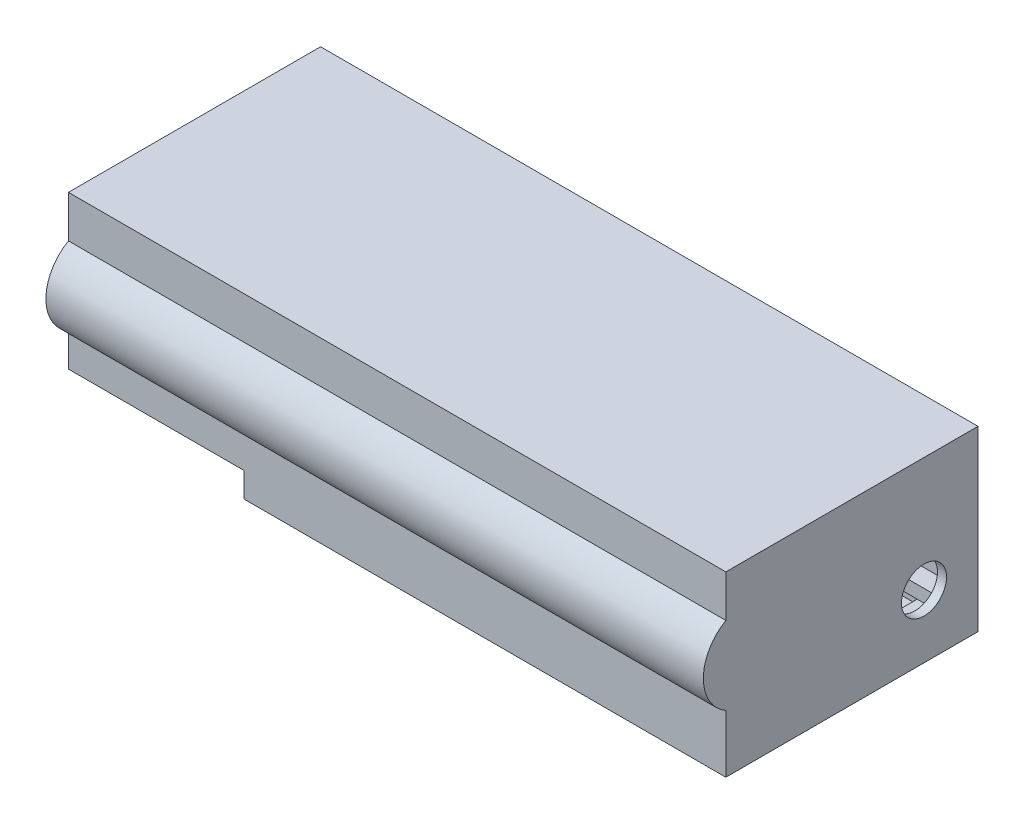
SolidWorks part; units mm, degrees
ref_plane "Front Plane" through (0, 0, 0) normal (0, 0, 1) x (1, 0, 0)
ref_plane "Top Plane" through (0, 0, 0) normal (0, 1, 0) x (1, 0, 0)
ref_plane "Right Plane" through (0, 0, 0) normal (1, 0, 0) x (0, 0, -1)
sketch "Sketch1" plane through (0, 0, 0) normal (1, 0, 0) x (0, 0, -1)
  line L0 (0, 39.5) -> (28, 39.5)
  line L1 (0, 55) -> (0, -55) construction
  line L2 (28, 39.5) -> (28, 0)
  line L3 (55, 0) -> (-55, 0) construction
  line L4 (28, 0) -> (22, 0)
  line L5 (22, 0) -> (22, 1.5)
  line L6 (22, 1.5) -> (25, 1.5)
  line L7 (25, 1.5) -> (25, 5.5)
  line L8 (25, 5.5) -> (22, 5.5)
  line L9 (22, 5.5) -> (22, 37.5)
  line L10 (22, 37.5) -> (0, 37.5)
  line L11 (0, 39.5) -> (0, 37.5)
  point P4 (0, 0)
  point P16 (0, 0)
  dimension "D1" = 2
  dimension "D2" = 6
  dimension "D3" = 3
  dimension "D4" = 22
  dimension "D5" = 4
  dimension "D6" = 1.5
  dimension "D7" = 32
extrude "Boss-Extrude1" add sketch "Sketch1" along normal blind 144
mirror "Mirror1" about plane through (0, 0, 0) normal (0, 0, 1) of "Boss-Extrude1"
sketch "Sketch2" plane through (144, 0, 0) normal (1, 0, 0) x (0, 0, -1)
  line L1 (22, 37.5) -> (26, 37.5)
  line L2 (22, 37.5) -> (22, 8.3284)
  line L3 (22, 8.3284) -> (26, 8.3284)
  line L4 (26, 37.5) -> (26, 8.3284)
  dimension "D1" = 4
  dimension "D2" = 3
extrude "Cut-Extrude1" cut sketch "Sketch2" against normal through all both and the other way through all
mirror "Mirror2" about plane through (0, 0, 0) normal (0, 0, 1) of "Cut-Extrude1"
sketch "Sketch3" plane through (144, 0, 0) normal (1, 0, 0) x (0, 0, -1)
  line L0 (-28, 0) -> (-28, 39.5) construction
  line L2 (-22, 5.5) -> (-25, 5.5) construction
  line L3 (-28, 30.1603) -> (-28, 12.8397)
  arc A0 (-28, 30.1603) -> (-28, 12.8397) centre (-23, 21.5) ccw
  point P7 (-28, 31.2777)
  dimension "D2" = 10
  dimension "D3" = 5
  dimension "D1" = 16
extrude "Boss-Extrude2" add sketch "Sketch3" against normal blind 144
sketch "Sketch4" plane through (144, 0, 0) normal (1, 0, 0) x (0, 0, -1)
  line L0 (-26, 37.5) -> (-26, 8.3284) construction
  line L1 (-26, 8.3284) -> (-22, 8.3284) construction
  line L2 (-26, 28.0366) -> (-26, 14.6202)
  arc A0 (-26, 28.0366) -> (-26, 14.6202) centre (-24, 21.3284) ccw
  dimension "D2" = 7
  dimension "D1" = 13
  dimension "D3" = 2
extrude "Cut-Extrude2" cut sketch "Sketch4" against normal through all both and the other way through all
sketch "Sketch6" plane through (0, 0, -28) normal (0, 0, -1) x (-1, 0, 0)
  line L0 (-39, 0) -> (-39, 5.5)
  line L2 (33.55, 0) -> (-33.55, 0) construction
  line L3 (-39, 5.5) -> (0, 5.5)
  line L4 (0, 21.725) -> (0, -21.725) construction
  line L5 (0, 5.5) -> (0, 0)
  line L6 (0, 0) -> (-39, 0)
  line L7 (-144, 0) -> (-144, 39.5) construction
  dimension "D1" = 105
  dimension "D2" = 5.5
extrude "Cut-Extrude3" cut sketch "Sketch6" against normal through all both and the other way through all
sketch "Sketch7" plane through (0, 0, -28) normal (0, 0, -1) x (-1, 0, 0)
  line L0 (-144, 39.5) -> (-146, 39.5)
  line L1 (-146, 39.5) -> (-146, 0)
  line L2 (33.55, 0) -> (-33.55, 0) construction
  line L3 (-146, 0) -> (-136, 0)
  line L4 (-136, 0) -> (-136, 2.9977)
  line L5 (-136, 2.9977) -> (-144, 2.9977)
  line L6 (-144, 0) -> (-144, 39.5) construction
  line L11 (-144, 2.9977) -> (-144, 39.5)
  point P3 (0, 0)
  point P13 (0, 0)
  dimension "D1" = 2.9977
  dimension "D4" = 10
  dimension "D5" = 8
extrude "Boss-Extrude3" add sketch "Sketch7" against normal up to vertex (56 mm away)
sketch "Sketch10" plane through (144, 0, 0) normal (1, 0, 0) x (0, 0, -1)
  line L0 (-28, 30.1603) -> (-28, 12.8397)
  arc A0 (-28, 30.1603) -> (-28, 12.8397) centre (-23, 21.5) ccw
  dimension "D1" = 10
extrude "Boss-Extrude5" add sketch "Sketch10" along normal blind 3
sketch "Sketch15" plane through (147, 0, 0) normal (1, 0, 0) x (0, 0, -1)
  line L0 (-28, 12.8397) -> (-28, 30.1603)
  arc A0 (-28, 12.8397) -> (-28, 30.1603) centre (-23, 21.5) cw
  dimension "D1" = 10
extrude "Cut-Extrude5" cut sketch "Sketch15" against normal blind 1
sketch "Sketch16" plane through (146, 0, 0) normal (1, 0, 0) x (0, 0, -1)
  line L0 (-28, 0) -> (28, 0) construction
  line L1 (28, 39.5) -> (28, 0) construction
  circle A0 centre (16, 14) radius 5
  dimension "D1" = 10
  dimension "D2" = 14
  dimension "D3" = 12
extrude "Cut-Extrude6" cut sketch "Sketch16" against normal through all both and the other way through all
sketch "Sketch17" plane through (0, 0, 0) normal (0, -1, 0) x (1, 0, 0)
  line L0 (39, 28) -> (39, 22) construction
  line L1 (39, 25) -> (121, 25)
  line L2 (39, 25) -> (39, -25)
  line L3 (39, -25) -> (121, -25)
  line L4 (121, 25) -> (121, -25)
  line L5 (136, -22) -> (39, -22) construction
  line L6 (136, 22) -> (136, -22) construction
  dimension "D1" = 3
  dimension "D2" = 15
extrude "Cut-Extrude7" cut sketch "Sketch17" against normal blind 3
sketch "Sketch18" plane through (0, 0, 0) normal (0, -1, 0) x (1, 0, 0)
  line L0 (146, 28) -> (146, -28) construction
  line L1 (-6.7122, 45.6424) -> (136, 45.6424)
  line L2 (-6.7122, 45.6424) -> (-6.7122, -44.4772)
  line L3 (-6.7122, -44.4772) -> (136, -44.4772)
  line L4 (136, 45.6424) -> (136, -44.4772)
  dimension "D1" = 10
